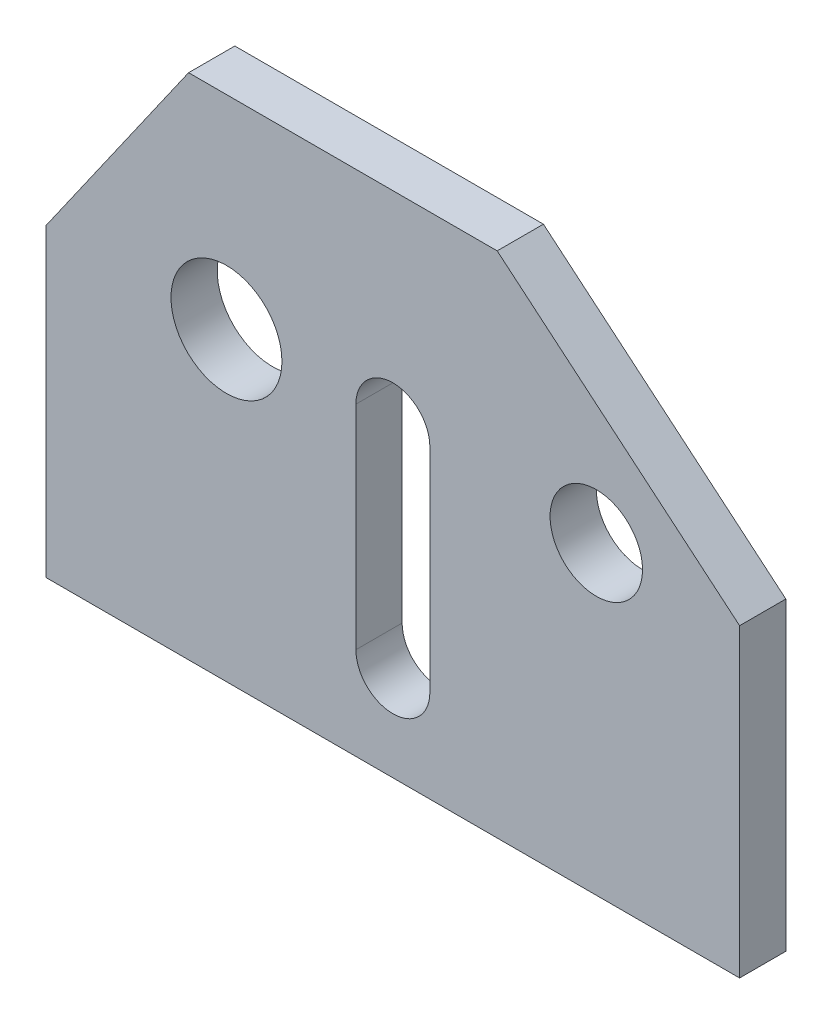
SolidWorks part; units mm, degrees
ref_plane "Front Plane" through (0, 0, 0) normal (0, 0, 1) x (1, 0, 0)
ref_plane "Top Plane" through (0, 0, 0) normal (0, 1, 0) x (1, 0, 0)
ref_plane "Right Plane" through (0, 0, 0) normal (1, 0, 0) x (0, 0, -1)
sketch "Sketch1" plane through (0, 0, 0) normal (0, 0, 1) x (1, 0, 0)
  line L0 (0, 0) -> (75, 0)
  line L1 (55, 0) -> (-55, 0) construction
  line L2 (75, 0) -> (75, 33)
  line L3 (75, 33) -> (48.7814, 55)
  line L4 (48.7814, 55) -> (15.4046, 55)
  line L5 (15.4046, 55) -> (0, 33)
  line L6 (0, -55) -> (0, 55) construction
  line L7 (0, 33) -> (0, 0)
  line L8 (33.5, 33) -> (33.5, 10)
  line L9 (41.5, 10) -> (41.5, 33)
  line L10 (0, 33) -> (75, 33) construction
  arc A0 (33.5, 10) -> (41.5, 10) centre (37.5, 10) ccw
  arc A1 (41.5, 33) -> (33.5, 33) centre (37.5, 33) ccw
  circle A2 centre (19.5, 33) radius 6
  circle A3 centre (59.5, 33) radius 5
  point P21 (0, 0)
  point P22 (0, 0)
  point P23 (0, 0)
  point P24 (36.0043, 10)
  dimension "D1" = 4
  dimension "D2" = 10
  dimension "D3" = 12
  dimension "D4" = 33
  dimension "D5" = 23
  dimension "D6" = 35
  dimension "D7" = 50
  dimension "D8" = 18
  dimension "D9" = 22
  dimension "D10" = 75
  dimension "D11" = 55
  dimension "D12" = 37.5
extrude "Boss-Extrude1" add sketch "Sketch1" along normal blind 5
